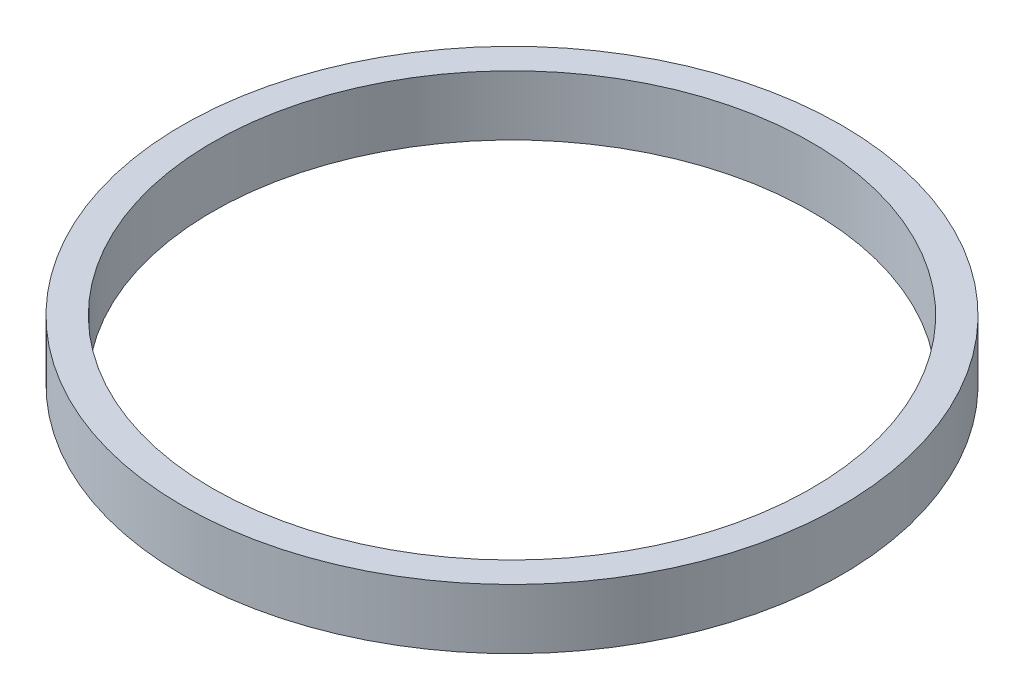
SolidWorks part; units mm, degrees
ref_plane "Front Plane" through (0, 0, 0) normal (0, 0, 1) x (1, 0, 0)
ref_plane "Top Plane" through (0, 0, 0) normal (0, 1, 0) x (1, 0, 0)
ref_plane "Right Plane" through (0, 0, 0) normal (1, 0, 0) x (0, 0, -1)
sketch "Sketch1" plane through (0, 0, 0) normal (0, 1, 0) x (1, 0, 0)
  circle A0 centre (0, 0) radius 33
  circle A1 centre (0, 0) radius 30
  dimension "D1" = 66
  dimension "D2" = 60
extrude "Boss-Extrude1" add sketch "Sketch1" along normal blind 6
